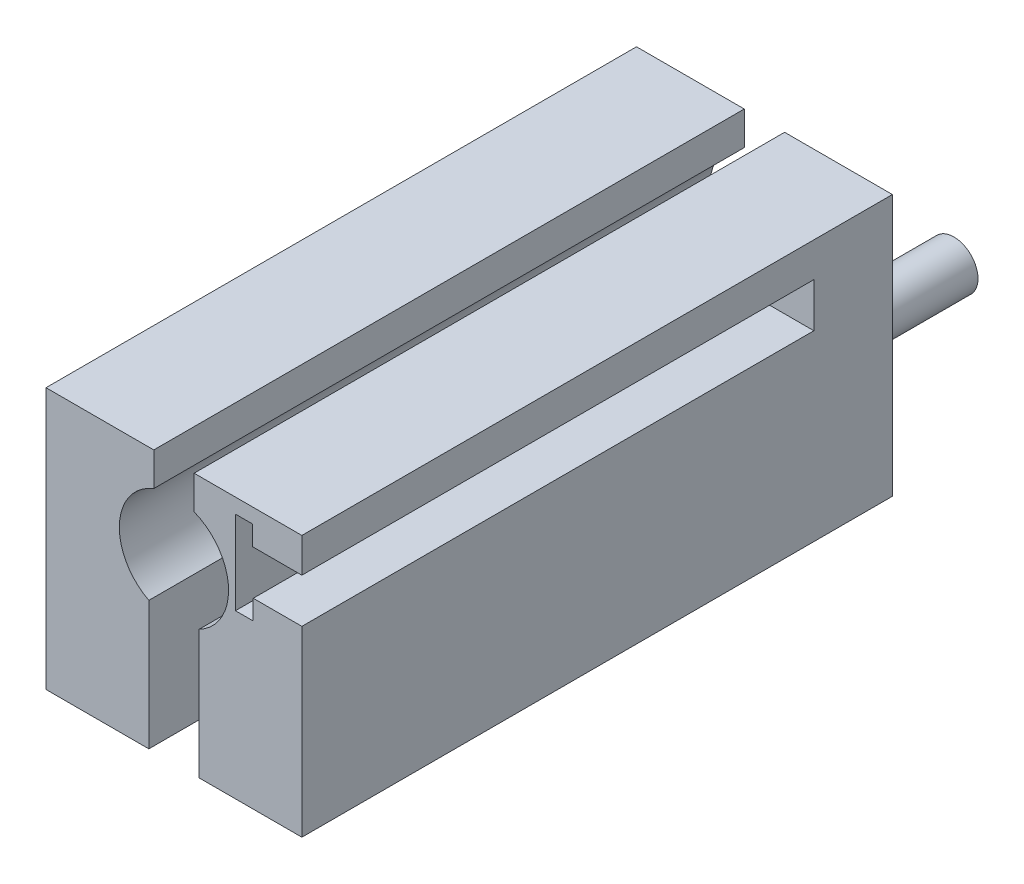
SolidWorks part; units mm, degrees
ref_plane "정면" through (0, 0, 0) normal (0, 0, 1) x (1, 0, 0)
ref_plane "윗면" through (0, 0, 0) normal (0, 1, 0) x (1, 0, 0)
ref_plane "우측면" through (0, 0, 0) normal (1, 0, 0) x (0, 0, -1)
sketch "스케치2" plane through (0, 0, 0) normal (0, 1, 0) x (1, 0, 0)
  line L1 (-26, -60) -> (26, -60)
  line L2 (-26, -60) -> (-26, 60)
  line L3 (-26, 60) -> (26, 60)
  line L4 (26, -60) -> (26, 60)
  line L5 (-26, -60) -> (26, 60) construction
  line L6 (-26, 60) -> (26, -60) construction
  point P0 (0, 0)
  dimension "D1" = 52
  dimension "D2" = 120
extrude "보스-돌출1" add sketch "스케치2" along normal mid plane 15
sketch "스케치3" plane through (0, 0, 0) normal (0, 0, 1) x (1, 0, 0)
  line L0 (0, 7.5) -> (0, 28.5) construction
  line L1 (-26, 7.5) -> (26, 7.5) construction
  line L2 (-26, 7.5) -> (-26, 32.5)
  line L3 (-26, 7.5) -> (26, 7.5)
  line L4 (26, 7.5) -> (26, 32.5)
  line L5 (-26, 32.5) -> (-9.6494, 43.219)
  line L6 (9.6494, 43.219) -> (26, 32.5)
  line L7 (-9.6494, 43.219) -> (9.6494, 43.219) construction
  circle A0 centre (0, 28.5) radius 11.1
  circle A1 centre (0, 28.5) radius 17.6
  dimension "D1" = 22.2
  dimension "D3" = 6.5
  dimension "D4" = 25
  dimension "D2" = 21
extrude "보스-돌출2" add sketch "스케치3" along normal mid plane 120
sketch "스케치4" plane through (0, 0, 0) normal (0, 0, 1) x (1, 0, 0)
  line L0 (0, 46.1) -> (0, 39.6) construction
  line L2 (-4.1, 38.815) -> (4.1, 38.815)
  line L3 (-4.1, 38.815) -> (-4.1, 46.885)
  line L4 (-4.1, 46.885) -> (4.1, 46.885)
  line L5 (4.1, 38.815) -> (4.1, 46.885)
  line L6 (-4.1, 38.815) -> (4.1, 46.885) construction
  line L7 (-4.1, 46.885) -> (4.1, 38.815) construction
  arc A0 (9.6494, 43.219) -> (-9.6494, 43.219) centre (0, 28.5) ccw construction
  circle A1 centre (0, 28.5) radius 11.1 construction
  point P8 (0, 42.85)
  dimension "D1" = 8.2
extrude "컷-돌출1" cut sketch "스케치4" against normal through all both and the other way through all
sketch "스케치5" plane through (0, 0, 60) normal (0, 0, 1) x (1, 0, 0)
  line L0 (0, 5.5705) -> (0, 0) construction
  line L1 (-5.1, -7.5) -> (5.1, -7.5)
  line L2 (-5.1, -7.5) -> (-5.1, 18.641)
  line L3 (-5.1, 18.641) -> (5.1, 18.641)
  line L4 (5.1, -7.5) -> (5.1, 18.641)
  line L5 (-5.1, -7.5) -> (5.1, 18.641) construction
  line L6 (-5.1, 18.641) -> (5.1, -7.5) construction
  line L7 (-26, -7.5) -> (26, -7.5) construction
  arc A0 (-4.1, 38.815) -> (4.1, 38.815) centre (0, 28.5) ccw construction
  point P0 (0, 5.5705)
  dimension "D1" = 10.2
extrude "컷-돌출2" cut sketch "스케치5" against normal blind 70
sketch "스케치6" plane through (0, 0, -60) normal (0, 0, -1) x (-1, 0, 0)
  line L0 (0, 0) -> (0, 14.5) construction
  line L1 (13.5, 14.5) -> (-13.5, 14.5) construction
  circle A0 centre (13.5, 14.5) radius 4.9
  circle A1 centre (-13.5, 14.5) radius 4.9
  point P6 (0, 14.5)
  dimension "D1" = 9.8
  dimension "D2" = 27
  dimension "D3" = 14.5
extrude "보스-돌출3" add sketch "스케치6" along normal blind 25
ref_plane "평면1" through (0, 0, 60) normal (0, 0, 1) x (1, 0, 0)
sketch "스케치9" plane through (0, 0, 60) normal (0, 0, 1) x (1, 0, 0)
  line L0 (-26, 32.5) -> (-26, 45.6158)
  line L1 (-26, 45.6158) -> (-4.1, 45.6158)
  line L2 (-4.1, 45.6158) -> (-6.9784, 44.6574)
  line L3 (-6.9784, 44.6574) -> (-26, 32.5)
  line L4 (26, 32.5) -> (26, 45.6158)
  line L5 (26, 45.6158) -> (4.1, 45.6158)
  line L6 (4.1, 45.6158) -> (6.9784, 44.6574)
  line L7 (6.9784, 44.6574) -> (26, 32.5)
  arc A0 (-4.1, 45.6158) -> (-9.6494, 43.219) centre (0, 28.5) ccw construction
  arc A1 (9.6494, 43.219) -> (4.1, 45.6158) centre (0, 28.5) ccw construction
  point P0 (-4.1, 45.6158)
  point P5 (4.1, 45.6158)
extrude "보스-돌출4" add sketch "스케치9" against normal up to vertex (120 mm away) contours L6 L7 L4 L5 | L1 L2 L3 L0 up to point (-26, 32.5, -60)
ref_plane "평면2" through (26, 0, 0) normal (1, 0, 0) x (0, 0, -1)
sketch "스케치10" plane through (26, 0, 0) normal (1, 0, 0) x (0, 0, -1)
  line L0 (-60, 45.6158) -> (-60, -7.5) construction
  line L1 (-60, 38.6158) -> (44.0445, 38.6158)
  line L2 (-60, 38.6158) -> (-60, 29.6158)
  line L3 (-60, 29.6158) -> (44.0445, 29.6158)
  line L4 (44.0445, 38.6158) -> (44.0445, 29.6158)
  line L5 (60, 45.6158) -> (-60, 45.6158) construction
  dimension "D1" = 9
  dimension "D2" = 7
sketch "스케치12" plane through (26, 0, 0) normal (1, 0, 0) x (0, 0, -1)
  point P1 (-60, 38.6158)
sketch "스케치13" plane through (0, 0, 60) normal (0, 0, 1) x (1, 0, 0)
  line L0 (26, 38.6158) -> (16, 38.6158)
  line L1 (16, 38.6158) -> (16, 42.6158)
  line L2 (16, 42.6158) -> (12.5, 42.6158)
  line L3 (12.5, 42.6158) -> (12.5, 25.6158)
  line L4 (12.5, 25.6158) -> (16.1167, 25.6158)
  line L5 (16.1167, 25.6158) -> (16.1167, 29.6158)
  line L6 (16.1167, 29.6158) -> (26, 29.6158)
  line L7 (26, 38.6158) -> (26, 29.6158) construction
  line L8 (26, 38.6158) -> (26, 29.6158)
  dimension "D1" = 10
  dimension "D2" = 4
  dimension "D3" = 4
  dimension "D4" = 3.5
  dimension "D5" = 9
extrude "컷-돌출3" cut sketch "스케치13" against normal up to vertex (104.0445 mm away) up to point (26, 29.6158, -44.0445)
